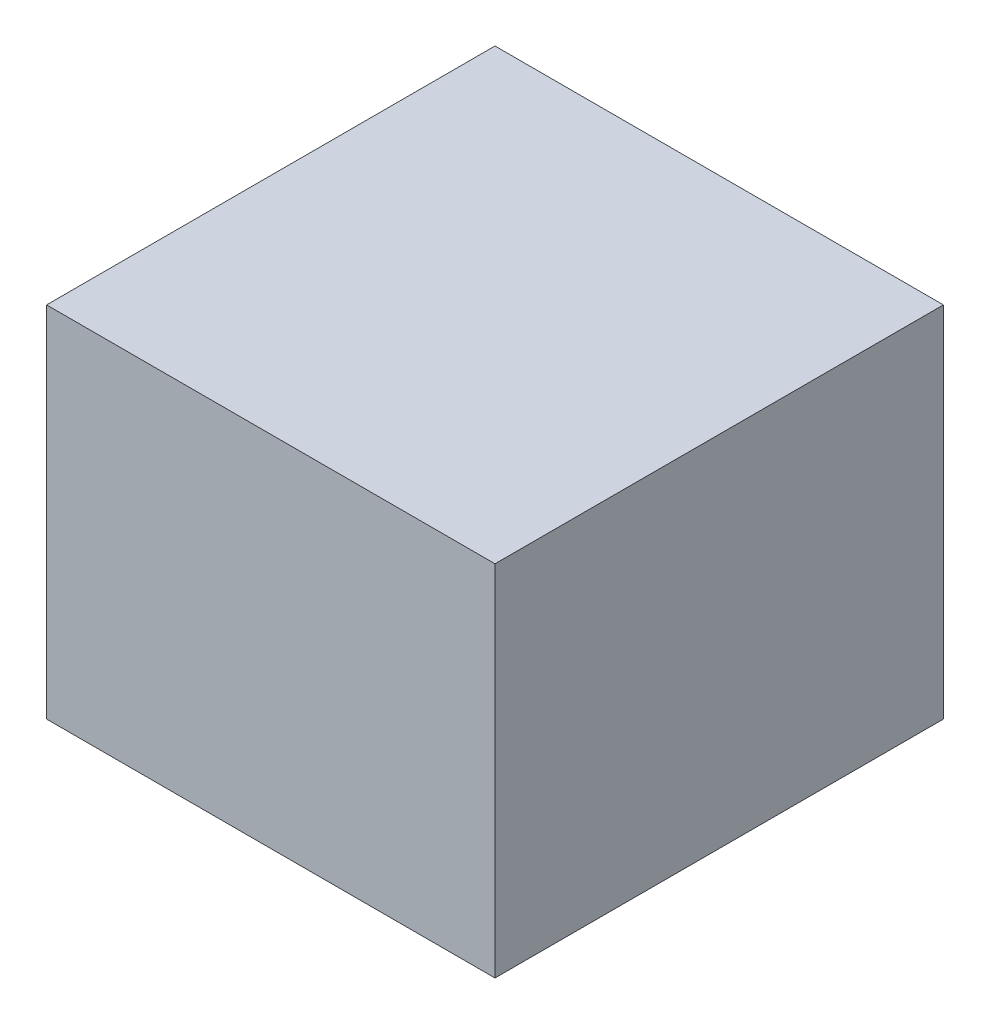
SolidWorks part; units mm, degrees
ref_plane "Спереди" through (0, 0, 0) normal (0, 0, 1) x (1, 0, 0)
ref_plane "Сверху" through (0, 0, 0) normal (0, 1, 0) x (1, 0, 0)
ref_plane "Справа" through (0, 0, 0) normal (1, 0, 0) x (0, 0, -1)
sketch "Эскиз1" plane through (0, 0, 0) normal (0, 1, 0) x (1, 0, 0)
  line L1 (0, 0) -> (50, 0)
  line L2 (0, 0) -> (0, -50)
  line L3 (0, -50) -> (50, -50)
  line L4 (50, 0) -> (50, -50)
  dimension "D1" = 50
  dimension "D2" = 50
extrude "Бобышка-Вытянуть1" add sketch "Эскиз1" along normal blind 40
